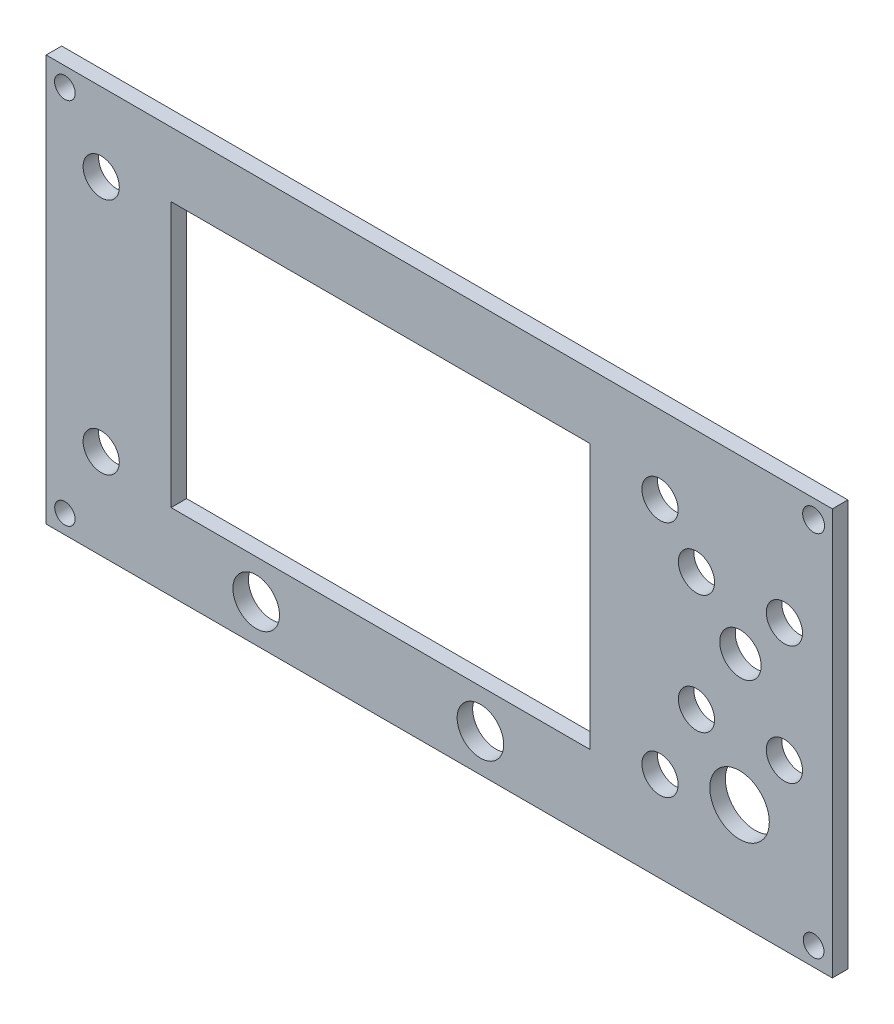
SolidWorks part; units mm, degrees
ref_plane "Plan de face" through (0, 0, 0) normal (0, 0, 1) x (1, 0, 0)
ref_plane "Plan de dessus" through (0, 0, 0) normal (0, 1, 0) x (1, 0, 0)
ref_plane "Plan de droite" through (0, 0, 0) normal (1, 0, 0) x (0, 0, -1)
sketch "Esquisse1" plane through (0, 0, 0.8) normal (0, 0, 1) x (1, 0, 0)
  line L0 (-95.6944, -23.7786) -> (-9.1944, -23.7786) construction
  line L1 (-112.5896, 39.9055) -> (24.8649, 39.9055)
  line L2 (-119.8323, 32.6629) -> (-119.8323, -31.3687)
  line L3 (-112.5896, -38.6114) -> (24.8649, -38.6114)
  line L4 (32.1075, 32.6629) -> (32.1075, -31.3687)
  line L5 (-95.6944, 27.4214) -> (-14.6944, 27.4214)
  line L6 (-95.6944, 27.4214) -> (-95.6944, -23.7786)
  line L7 (-95.6944, -23.7786) -> (-14.6944, -23.7786)
  line L8 (-14.6944, 27.4214) -> (-14.6944, -23.7786)
  line L9 (-15.1944, -23.2786) -> (-15.1944, 26.9214) construction
  line L10 (-119.8323, 39.9055) -> (-115.5896, 35.6629) construction
  line L11 (-112.5896, 35.6629) -> (-112.5896, 39.9055)
  line L12 (-115.5896, 32.6629) -> (-119.8323, 32.6629)
  line L13 (-43.8624, -38.6114) -> (-43.8624, 39.9055) construction
  line L14 (32.1075, 0.6471) -> (-119.8323, 0.6471) construction
  line L15 (24.8649, 35.6629) -> (24.8649, 39.9055)
  line L16 (27.8649, 32.6629) -> (32.1075, 32.6629)
  line L17 (-112.5896, -34.3687) -> (-112.5896, -38.6114)
  line L18 (-115.5896, -31.3687) -> (-119.8323, -31.3687)
  line L19 (24.8649, -34.3687) -> (24.8649, -38.6114)
  line L20 (27.8649, -31.3687) -> (32.1075, -31.3687)
  line L21 (32.1075, -38.6114) -> (32.1075, 39.9055) construction
  line L22 (-119.8323, -38.6114) -> (32.1075, -38.6114) construction
  line L23 (-119.8323, -31.3687) -> (-115.5896, -31.3687) construction
  circle A0 centre (-109.1944, 24.8214) radius 3.5
  circle A1 centre (-1.1944, 24.8214) radius 3.5
  circle A2 centre (-1.1944, -21.1786) radius 3.5
  circle A3 centre (-109.1944, -21.1786) radius 3.5
  arc A4 (-115.5896, 32.6629) -> (-112.5896, 35.6629) centre (-115.5896, 35.6629) ccw
  arc A5 (27.8649, 32.6629) -> (24.8649, 35.6629) centre (27.8649, 35.6629) cw
  arc A6 (-115.5896, -31.3687) -> (-112.5896, -34.3687) centre (-115.5896, -34.3687) cw
  arc A7 (27.8649, -31.3687) -> (24.8649, -34.3687) centre (27.8649, -34.3687) ccw
  circle A8 centre (14.3452, 6.7499) radius 4
  circle A9 centre (5.8452, 16.2043) radius 3.5
  circle A10 centre (22.8452, 16.2043) radius 3.5
  circle A11 centre (22.8452, -6.7957) radius 3.5
  circle A12 centre (5.8452, -6.7957) radius 3.5
  circle A13 centre (14.1766, -18.6114) radius 5.75
  circle A15 centre (-35.9056, -31.3167) radius 4.5
  circle A16 centre (-79.2375, -31.3167) radius 4.5
  circle A17 centre (-109.1944, 24.8214) radius 2 construction
  circle A18 centre (-109.1944, -21.1786) radius 2 construction
  circle A19 centre (-1.1944, -21.1786) radius 2 construction
  circle A20 centre (-1.1944, 24.8214) radius 2 construction
  point P72 (32.1075, 0.6471)
  dimension "D1" = 7
  dimension "D4" = 6
  dimension "D6" = 11.5
  dimension "D7" = 9
  dimension "D8" = 9
  dimension "D2" = 0.5
  dimension "D3" = 45
  dimension "D5" = 6
extrude "Boss.-Extru.1" add sketch "Esquisse1" along normal blind 3
sketch "Esquisse2" plane through (0, 0, 0.8) normal (0, 0, 1) x (1, 0, 0)
  line L1 (-112.5896, -38.6114) -> (-119.8323, -38.6114)
  line L2 (-112.5896, -38.6114) -> (-112.5896, -31.3687)
  line L3 (-112.5896, -31.3687) -> (-119.8323, -31.3687)
  line L4 (-119.8323, -38.6114) -> (-119.8323, -31.3687)
  line L5 (-112.5896, 39.9055) -> (-119.8323, 39.9055)
  line L6 (-112.5896, 39.9055) -> (-112.5896, 32.6629)
  line L7 (-112.5896, 32.6629) -> (-119.8323, 32.6629)
  line L8 (-119.8323, 39.9055) -> (-119.8323, 32.6629)
  line L9 (24.8649, 39.9055) -> (32.1075, 39.9055)
  line L10 (24.8649, 39.9055) -> (24.8649, 32.6629)
  line L11 (24.8649, 32.6629) -> (32.1075, 32.6629)
  line L12 (32.1075, 39.9055) -> (32.1075, 32.6629)
  line L13 (32.1075, -31.3687) -> (24.8649, -31.3687)
  line L14 (32.1075, -31.3687) -> (32.1075, -38.6114)
  line L15 (32.1075, -38.6114) -> (24.8649, -38.6114)
  line L16 (24.8649, -31.3687) -> (24.8649, -38.6114)
  circle A0 centre (-116.211, -34.9901) radius 1.9653
  circle A1 centre (28.4862, 36.2842) radius 2.1135
  circle A2 centre (-116.211, 36.2842) radius 2
  circle A3 centre (28.4862, -34.9901) radius 2
extrude "Boss.-Extru.2" add sketch "Esquisse2" along normal blind 3
